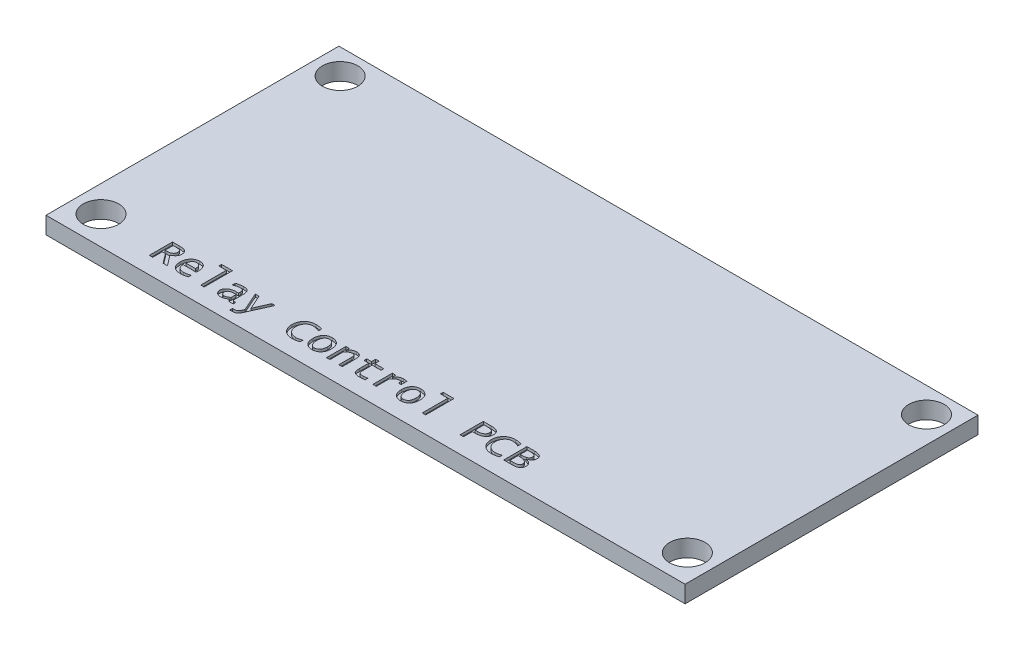
SolidWorks part; units mm, degrees
ref_plane "Front Plane" through (0, 0, 0) normal (0, 0, 1) x (1, 0, 0)
ref_plane "Top Plane" through (0, 0, 0) normal (0, 1, 0) x (1, 0, 0)
ref_plane "Right Plane" through (0, 0, 0) normal (1, 0, 0) x (0, 0, -1)
sketch "Sketch1" plane through (0, 0, 0) normal (0, 1, 0) x (1, 0, 0)
  line L1 (0, 0) -> (60.96, 0)
  line L2 (0, 0) -> (0, 27.94)
  line L3 (0, 27.94) -> (60.96, 27.94)
  line L4 (60.96, 0) -> (60.96, 27.94)
  dimension "D1" = 60.96
  dimension "D2" = 27.94
extrude "Boss-Extrude1" add sketch "Sketch1" along normal blind 1.6256
sketch "Sketch2" plane through (0, 1.6256, 0) normal (0, 1, 0) x (1, 0, 0)
  line L0 (60.96, 27.94) -> (0, 27.94) construction
  line L2 (0, 0) -> (60.96, 0) construction
  line L3 (0, 27.94) -> (0, 0) construction
  line L4 (60.96, 0) -> (60.96, 27.94) construction
  circle A0 centre (2.5273, 25.527) radius 1.6891
  circle A1 centre (2.5273, 2.7178) radius 1.6891
  circle A2 centre (58.4581, 25.527) radius 1.6891
  circle A3 centre (58.4581, 2.7178) radius 1.6891
  dimension "D1" = 3.3782
  dimension "D2" = 3.3782
  dimension "D3" = 3.3782
  dimension "D4" = 3.3782
  dimension "D5" = 2.5019
  dimension "D9" = 2.5273
  dimension "D10" = 2.7178
  dimension "D11" = 2.5273
  dimension "D12" = 2.413
extrude "Cut-Extrude1" cut sketch "Sketch2" against normal blind 1.6256
sketch "Sketch3" plane through (0, 1.6256, 0) normal (0, 1, 0) x (1, 0, 0)
  text T0 "Relay Control PCB" font "Lucida Console" height in points 8
extrude "Cut-Extrude2" cut sketch "Sketch3" against normal blind 0.254
